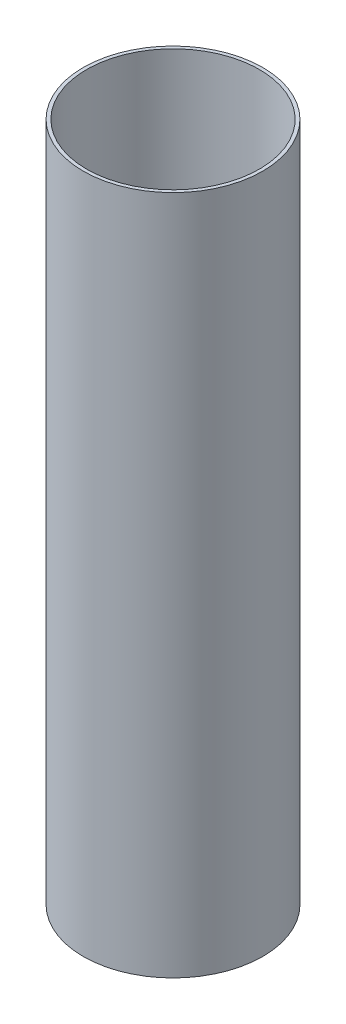
SolidWorks part; units mm, degrees
ref_plane "Front Plane" through (0, 0, 0) normal (0, 0, 1) x (1, 0, 0)
ref_plane "Top Plane" through (0, 0, 0) normal (0, 1, 0) x (1, 0, 0)
ref_plane "Right Plane" through (0, 0, 0) normal (1, 0, 0) x (0, 0, -1)
sketch "Sketch1" plane through (0, 0, 0) normal (0, 1, 0) x (1, 0, 0)
  circle A0 centre (0, 0) radius 38.1
  circle A1 centre (0, 0) radius 39.6
  dimension "D1" = 76.2
  dimension "D2" = 1.5
extrude "Boss-Extrude1" add sketch "Sketch1" along normal blind 300
